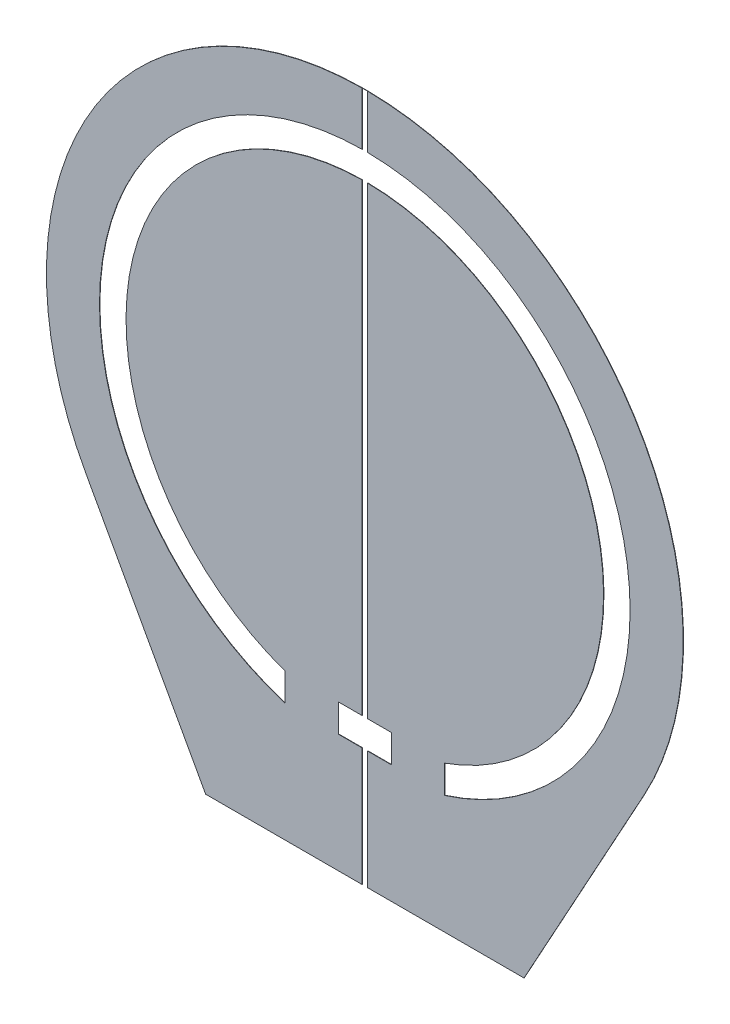
SolidWorks part; units mm, degrees
ref_plane "Plano frontal" through (0, 0, 0) normal (0, 0, 1) x (1, 0, 0)
ref_plane "Plano superior" through (0, 0, 0) normal (0, 1, 0) x (1, 0, 0)
ref_plane "Plano direito" through (0, 0, 0) normal (1, 0, 0) x (0, 0, -1)
sketch "Sketch2" plane through (0, 0, 0) normal (0, 0, 1) x (1, 0, 0)
  line L0 (0.25, -21.2132) -> (2.5, -21.2132)
  line L1 (0, -35) -> (-15, -35)
  line L2 (-15, -35) -> (-7.5, -35)
  line L3 (-7.5, -21.2132) -> (-7.5, -23.8485)
  line L4 (-2.5, -21.2132) -> (-0.25, -21.2132)
  line L5 (7.5, -21.2132) -> (7.5, -23.8485)
  line L6 (7.5, -35) -> (0, -35)
  line L8 (-0.25, -21.2132) -> (-0.25, 22.4986)
  line L9 (0.25, -21.2132) -> (0.25, 22.4986)
  line L10 (-15, -35) -> (-26.2929, -14.4459)
  line L11 (15, -35) -> (26.2929, -14.4459)
  line L13 (-2.5, -21.2132) -> (-2.5, -23.8485)
  line L14 (2.5, -21.2132) -> (2.5, -23.8485)
  line L15 (-2.5, -23.8485) -> (2.5, -23.8485)
  line L20 (0, -35) -> (15, -35)
  arc A0 (-0.25, 22.4986) -> (-7.5, -21.2132) centre (0, 0) ccw
  arc A2 (7.5, -21.2132) -> (0.25, 22.4986) centre (0, 0) ccw
  arc A3 (7.5, -23.8485) -> (-7.5, -23.8485) centre (0, 0) ccw
  arc A4 (26.2929, -14.4459) -> (-26.2929, -14.4459) centre (0, 0) ccw
  point P14 (0, -21.2132)
  dimension "D1" = 45
  dimension "D3" = 50
  dimension "D11" = 60
  dimension "D4" = 15
  dimension "D5" = 0.5
  dimension "D6" = 5
  dimension "D7" = 5
  dimension "D8" = 2.6353
  dimension "D9" = 2.6353
  dimension "D10" = 15
extrude "Boss-Extrude1" add sketch "Sketch2" along normal blind 0.0356
sketch "Sketch3" plane through (0, 0, 0.0356) normal (0, 0, 1) x (1, 0, 0)
  line L0 (-0.25, 22.4986) -> (0.25, 22.4986)
  line L1 (-0.25, 22.4986) -> (-0.25, 29.999)
  line L2 (-0.25, 29.999) -> (0.25, 29.999)
  line L3 (0.25, 22.4986) -> (0.25, 29.999)
  line L4 (-0.25, -21.2132) -> (0.25, -21.2132)
  line L5 (0.25, -21.2132) -> (0.25, -35)
  line L6 (15, -35) -> (-15, -35) construction
  line L7 (-0.25, -21.2132) -> (-0.25, -35)
  line L8 (-0.25, -35) -> (0.25, -35)
  arc A0 (26.2929, -14.4459) -> (-26.2929, -14.4459) centre (0, 0) ccw construction
  dimension "D1" = 0.5
extrude "Cut-Extrude2" cut sketch "Sketch3" against normal blind 1 contours L2 L3 L0 L1 | L8 L5 L4 L7
